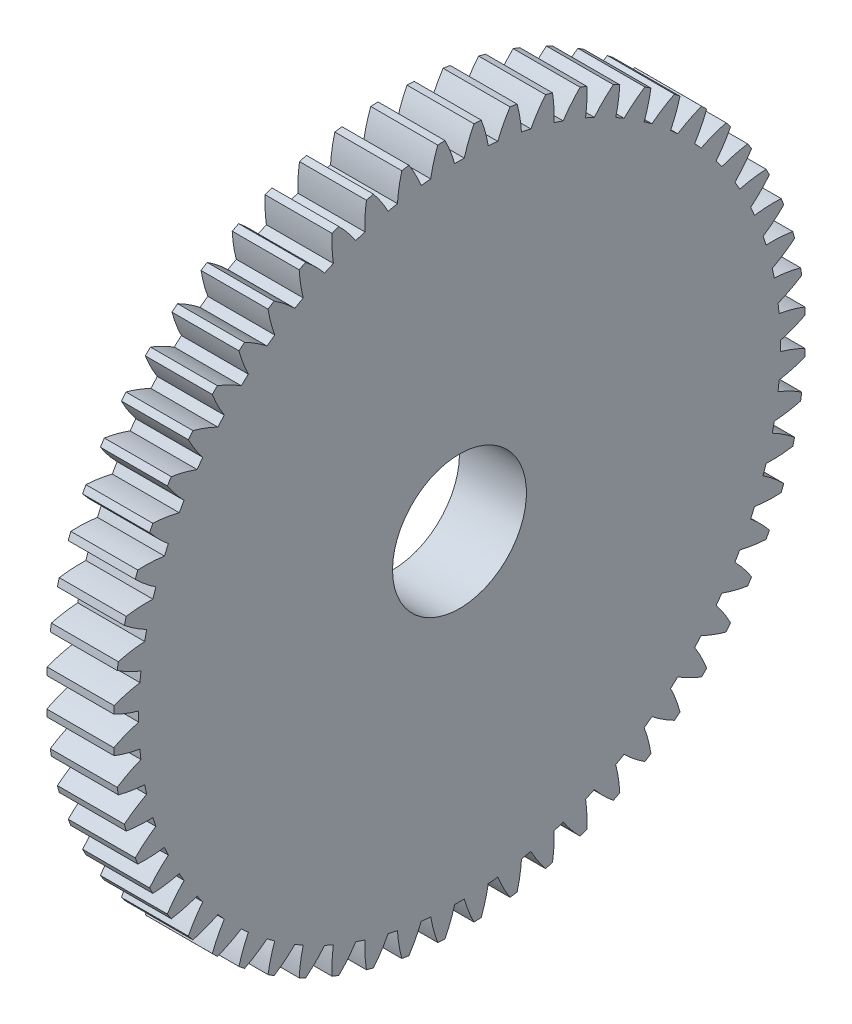
SolidWorks part; units mm, degrees
ref_plane "Plane1" through (0, 0, 0) normal (0, 0, 1) x (1, 0, 0)
ref_plane "Plane2" through (0, 0, 0) normal (0, 1, 0) x (1, 0, 0)
ref_plane "Plane3" through (0, 0, 0) normal (1, 0, 0) x (0, 0, -1)
sketch "HoldingSke" plane through (0, 0, 0) normal (0, 1, 0) x (1, 0, 0)
  line L0 (0, 0) -> (1, -1.7321)
  line L1 (-15, 0) -> (100, 0) construction
  line L2 (0, 0) -> (-2.1039, 2.3779)
  line L3 (0, 0) -> (-11.863, 4.5341)
  line L4 (0, 0) -> (4.318, 7.479)
  line L5 (0, 0) -> (-46.8476, -17.4728)
  line L6 (0, 0) -> (-2.4869, -1.6779)
  line L7 (-2.1039, 2.3779) -> (8.6586, 51.2059)
  line L8 (-76.2, 54.61) -> (-75.2, 54.61)
  line L9 (-71.009, 38.7566) -> (-53.1078, 45.2721)
  line L10 (-76.2, 71.12) -> (104.1128, 71.12)
  line L11 (0, 0) -> (-3, 0)
  line L12 (-76.2, 101.6) -> (-76.181, 101.6)
  line L13 (24.9733, 27.94) -> (52.9518, 28.4284)
  line L14 (24.9733, 27.94) -> (24.9743, 27.94)
  line L15 (24.9733, 27.94) -> (100.4006, 29.5858)
  line L16 (-63.627, -0.5) -> (-12.827, -0.5)
  circle A0 centre (0, 0) radius 3
  circle A1 centre (0, 0) radius 14.374
  circle A2 centre (0, 0) radius 37.5
  circle A3 centre (0, 0) radius 3
  dimension "MHD" = 28.748
  dimension "Hub_dia" = 75
  dimension "Bore" = 6
  dimension "MBD" = 6
  dimension "Num_teeth" = 60
  dimension "Pitch" = 2
  dimension "Overall_len" = 50
  dimension "Show_teeth" = 60
  dimension "Thickness" = 3
  dimension "OAL" = 50.0001
  dimension "T_dim" = 1
  dimension "Ap" = 20
  dimension "H" = 19.05
  dimension "Pitch_radius" = 180.3128
  dimension "Width" = 3
  dimension "Backlash" = 0.019
  dimension "Addendum_fac" = 1
  dimension "Dedendum_fac" = 1.25
  dimension "Clearance_fac" = 0.25
  dimension "Dedendum_add" = 0.001
  dimension "Module" = 0.5
sketch "BasProSke" plane through (0, 0, 0) normal (0, 1, 0) x (1, 0, 0)
  line L0 (-10, 0) -> (60, 0) construction
  line L1 (0, 0) -> (0, 15.5)
  line L2 (0, 0) -> (3, 0)
  line L3 (3, 0) -> (3, 15.5)
  line L4 (3, 15.5) -> (0, 15.5)
  dimension "Thickness" = 3
  dimension "Diameter" = 31
revolve "Base-Revolve" add sketch "BasProSke" angle 360 about L0
sketch "TooCutSke" plane through (0, 0, 0) normal (1, 0, 0) x (0, 0, -1)
  line L1 (0, 0) -> (0, 107) construction
  line L2 (0, 0) -> (-0.4259, 14.994) construction
  line L3 (0, 0) -> (-1.5696, 29.9503) construction
  line L4 (-0.4259, 14.994) -> (-0.7848, 14.9751) construction
  arc A0 (0.2149, 14.3724) -> (-0.2149, 14.3724) centre (0, 0) ccw
  arc A1 (0.6627, 15.5112) -> (-0.6627, 15.5112) centre (0, 0) ccw
  circle A2 centre (0, 0) radius 15 construction
  circle A3 centre (0, 0) radius 14.0954 construction
  arc A4 (-0.2149, 14.3724) -> (-0.6627, 15.5112) centre (-5.9936, 12.7576) ccw
  arc A5 (0.6627, 15.5112) -> (0.2149, 14.3724) centre (5.9936, 12.7576) ccw
  dimension "Root_dia" = 28.748
  dimension "Overcut_dia" = 31.0508
  dimension "Pitch_dia" = 30
  dimension "Base_dia" = 28.1908
  dimension "Flank_rad" = 6
  dimension "Half_ang" = 3
  dimension "Half_CT" = 0.3594
extrude "ToothCut" cut sketch "TooCutSke" along normal through all
fillet "Breaks" [suppressed] radius 0.01
fillet "RootFillets" [suppressed] radius 0.126
pattern_circular "TeethCuts" count 60 every 6 about axis through (-10, 0, 0) along (1, 0, 0) of "ToothCut", "RootFillets", "Breaks"
sketch "HubNeaOneSke" plane through (0, 0, 0) normal (-1, 0, 0) x (0, 0, 1)
  circle A0 centre (0, 0) radius 14.374
  dimension "Diameter" = 28.748
extrude "HubNearOne" [suppressed] add sketch "HubNeaOneSke" along normal blind 47.0001
sketch "HubNeaBotSke" plane through (0, 0, 0) normal (-1, 0, 0) x (0, 0, 1)
  circle A0 centre (0, 0) radius 14.374
  dimension "Diameter" = 28.748
extrude "HubNearBoth" [suppressed] add sketch "HubNeaBotSke" along normal blind 23.5
ref_plane "FarPln" through (3, 0, 0) normal (1, 0, 0) x (0, 0, -1)
sketch "HubFarSke" plane through (3, 0, 0) normal (1, 0, 0) x (0, 0, -1)
  circle A0 centre (0, 0) radius 14.374
  dimension "Diameter" = 28.748
extrude "HubFar" [suppressed] add sketch "HubFarSke" along normal blind 23.5
sketch "BorSke" plane through (0, 0, 0) normal (1, 0, 0) x (0, 0, -1)
  circle A0 centre (0, 0) radius 3
  dimension "Diameter" = 6
extrude "Bore" cut sketch "BorSke" along normal mid plane 100.0001
sketch "KeySke" plane through (0, 0, 0) normal (1, 0, 0) x (0, 0, -1)
  line L0 (-1, 0) -> (-1, 4)
  line L1 (-1, 4) -> (1, 4)
  line L2 (1, 4) -> (1, 0)
  line L3 (0, 0) -> (0, 34) construction
  line L4 (-1, 0) -> (1, 0)
  dimension "Offset" = 4
  dimension "Width" = 2
extrude "Keyway" [suppressed] cut sketch "KeySke" along normal mid plane 100.0001
pattern_circular "Keyway2" [suppressed] count 2 every 90 about axis through (-10, 0, 0) along (1, 0, 0)
equation "' \"Module@HoldingSke\" = 6.35"
equation "' \"Num_teeth@HoldingSke\" = 12"
equation "' \"Ap@HoldingSke\" =  20"
equation "' \"Ap@HoldingSke\" = 20"
equation "' \"Width@HoldingSke\" = 0.5 * 25.4"
equation "' \"Hub_dia@HoldingSke\"= 1 * 25.4"
equation "' \"Hub_dia@HoldingSke\" = 1 * 25.4"
equation "' \"Overall_len@HoldingSke\" = 1.0 * 25.4"
equation "' \"Bore@HoldingSke\" = 0.75 * 25.4"
equation "' \"T_dim@HoldingSke\" = 0.1 * 25.4"
equation "' \"Width@KeySke\" = 0.25 * 25.4"
equation "' \"Show_teeth@HoldingSke\" = 13"
equation "' \"Backlash@HoldingSke\" = 0.009 * 25.4"
equation "' \"Addendum_fac@HoldingSke\" = 1.0"
equation "' \"Dedendum_fac@HoldingSke\" = 1.25"
equation "' \"Dedendum_add@HoldingSke\" = 0.00005 * 25.4"
equation "' \"Clearance_fac@HoldingSke\" = 0.25"
equation "\"Pitch@HoldingSke\" = 1 / \"Module@HoldingSke\""
equation "\"Overcut_dia@TooCutSke\" = (\"Num_teeth@HoldingSke\" + 2 * \"Addendum_fac@HoldingSke\") / \"Pitch@HoldingSke\" + 0.002 * 25.4"
equation "\"Pitch_dia@TooCutSke\" = \"Num_teeth@HoldingSke\" / \"Pitch@HoldingSke\""
equation "\"Base_dia@TooCutSke\" = \"Num_teeth@HoldingSke\" / \"Pitch@HoldingSke\" * cos((\"Ap@HoldingSke\"  * 3.14159265 / 180))"
equation "\"Root_dia@TooCutSke\" = (\"Num_teeth@HoldingSke\" + 2) / \"Pitch@HoldingSke\" - 2 * (\"Addendum_fac@HoldingSke\" + \"Dedendum_fac@HoldingSke\") / \"Pitch@HoldingSke\" - \"Dedendum_add@HoldingSke\" * 2"
equation "\"Half_ang@TooCutSke\" = 180 / \"Num_teeth@HoldingSke\""
equation "\"Half_CT@TooCutSke\" = \"Num_teeth@HoldingSke\" / \"Pitch@HoldingSke\" * sin((3.14159265 / 2 / \"Num_teeth@HoldingSke\")) / 2 - 7 * \"Backlash@HoldingSke\" / 4"
equation "\"Flank_rad@TooCutSke\" = \"Num_teeth@HoldingSke\" / \"Pitch@HoldingSke\" / 5"
equation "\"Radius@RootFillets\" = \"Clearance_fac@HoldingSke\" / \"Pitch@HoldingSke\" + \"Dedendum_add@HoldingSke\""
equation "\"Break_rad@Breaks\" = 0.02 / \"Pitch@HoldingSke\""
equation "\"Thickness@HoldingSke\" = \"Width@HoldingSke\""
equation "\"OAL@HoldingSke\" = \"Thickness@HoldingSke\""
equation "\"MHD@HoldingSke\" = (\"Num_teeth@HoldingSke\" + 2) / \"Pitch@HoldingSke\" - 2 * (\"Addendum_fac@HoldingSke\" + \"Dedendum_fac@HoldingSke\")  / \"Pitch@HoldingSke\" - \"Dedendum_add@HoldingSke\" * 2"
equation "\"MBD@HoldingSke\" = (\"Num_teeth@HoldingSke\" + 2) / \"Pitch@HoldingSke\" - 2 * (\"Addendum_fac@HoldingSke\" + \"Dedendum_fac@HoldingSke\")  / \"Pitch@HoldingSke\" - \"Dedendum_add@HoldingSke\" * 2 - 0.002 * 25.4"
equation "\"MHD@HoldingSke\" = ((sgn( \"MHD@HoldingSke\" - \"Hub_dia@HoldingSke\" )-1)*( \"MHD@HoldingSke\" - \"Hub_dia@HoldingSke\" ))/-2+ \"Hub_dia@HoldingSke\""
equation "\"MBD@HoldingSke\" = ((sgn( \"MBD@HoldingSke\" - \"Bore@HoldingSke\" )-1)*( \"MBD@HoldingSke\" - \"Bore@HoldingSke\" ))/-2+ \"Bore@HoldingSke\""
equation "\"OAL@HoldingSke\" = ((sgn( \"OAL@HoldingSke\" - \"Overall_len@HoldingSke\" )+1)*( \"OAL@HoldingSke\" - \"Overall_len@HoldingSke\" ))/2 + \"Overall_len@HoldingSke\" + 0.000002 * 25.4"
equation "\"Num_teeth@TeethCuts\" = int( \"Show_teeth@HoldingSke\" ) + 1"
equation "\"Num_teeth@TeethCuts\" = ((sgn( \"Num_teeth@TeethCuts\" - \"Num_teeth@HoldingSke\" )-1)*( \"Num_teeth@TeethCuts\" - \"Num_teeth@HoldingSke\" ))/-2+ \"Num_teeth@HoldingSke\""
equation "\"Num_teeth@TeethCuts\" = ((sgn( \"Num_teeth@TeethCuts\" - 2.0)+1)*( \"Num_teeth@TeethCuts\" - 2.0))/2 +2.0"
equation "\"Angle@TeethCuts\" = 360.0 / \"Num_teeth@HoldingSke\""
equation "\"Diameter@BasProSke\" = (\"Num_teeth@HoldingSke\" + 2 * \"Addendum_fac@HoldingSke\") / \"Pitch@HoldingSke\""
equation "\"Thickness@BasProSke\"  = \"Thickness@HoldingSke\""
equation "' \"Fillet_rad@BasProSke\" =  \"Thickness@HoldingSke\" * 0.05"
equation "' \"Fillet_rad@BasProSke\" = \"Thickness@HoldingSke\" * 0.05"
equation "\"MHD@HoldingSke\" = ((sgn( \"MHD@HoldingSke\" - \"Root_dia@TooCutSke\" )-1)*( \"MHD@HoldingSke\" - \"Root_dia@TooCutSke\" ))/-2+ \"Root_dia@TooCutSke\""
equation "\"Diameter@HubNeaOneSke\" = \"MHD@HoldingSke\""
equation "\"Length@HubNearOne\" = \"OAL@HoldingSke\" - \"Thickness@BasProSke\""
equation "\"Diameter@HubNeaBotSke\" = \"MHD@HoldingSke\""
equation "\"Length@HubNearBoth\" = ( \"OAL@HoldingSke\" - \"Thickness@BasProSke\" ) / 2.0"
equation "\"Thickness@FarPln\" = \"Thickness@BasProSke\""
equation "\"Diameter@HubFarSke\" = \"MHD@HoldingSke\""
equation "\"Length@HubFar\" = ( \"OAL@HoldingSke\" - \"Thickness@BasProSke\" ) / 2.0"
equation "\"Diameter@BorSke\" = \"MBD@HoldingSke\""
equation "\"D1@Bore\" = \"OAL@HoldingSke\" * 2.0"
equation "\"D1@Keyway\" = \"OAL@HoldingSke\" * 2.0"
equation "\"Offset@KeySke\" = \"T_dim@HoldingSke\" + \"MBD@HoldingSke\" / 2.0"
